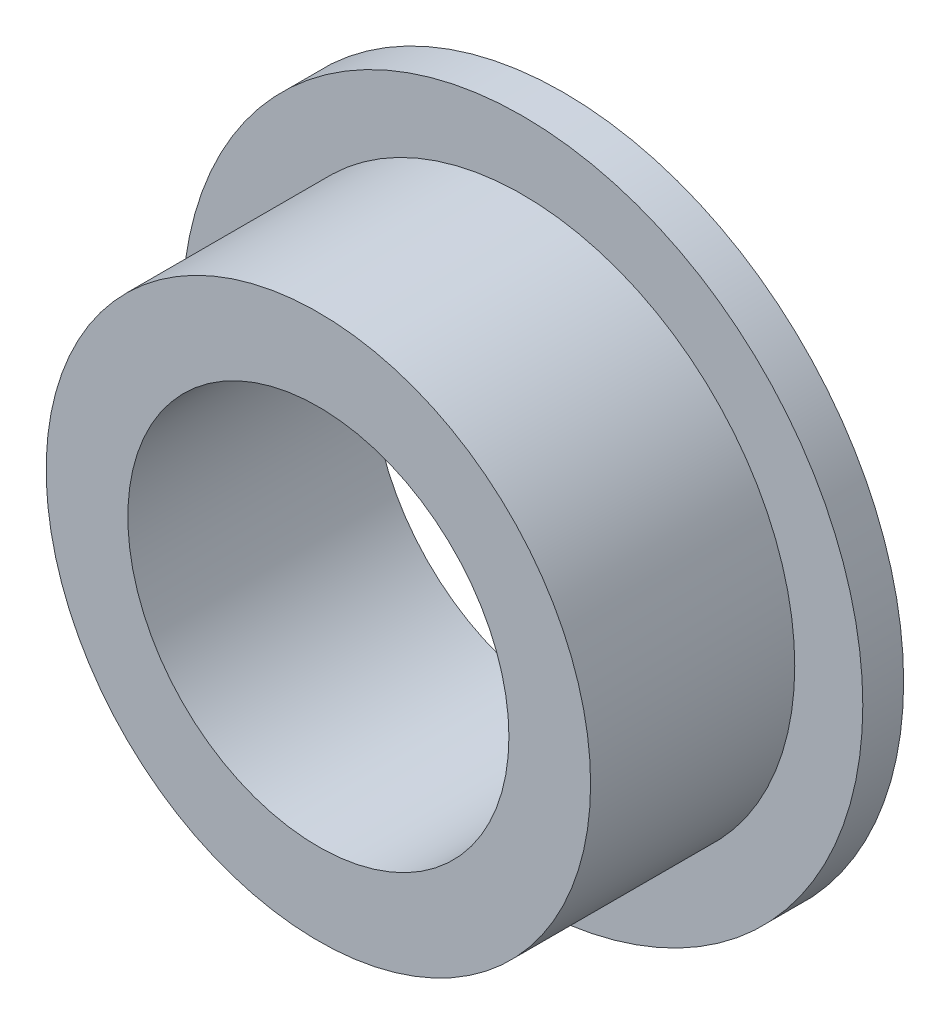
SolidWorks part; units mm, degrees
other "MotorBear"
material "Brass"
ref_plane "Front" through (0, 0, 0) normal (0, 0, 1) x (1, 0, 0)
ref_plane "Top" through (0, 0, 0) normal (0, 1, 0) x (1, 0, 0)
ref_plane "Right" through (0, 0, 0) normal (1, 0, 0) x (0, 0, -1)
sketch "Sketch1" plane through (0, 0, 0) normal (0, 0, 1) x (1, 0, 0)
  circle A0 centre (0, 0) radius 1.4
  circle A1 centre (0, 0) radius 2.5
  dimension "D1" = 2.8
  dimension "D2" = 5
extrude "Boss-Extrude1" add sketch "Sketch1" along normal blind 0.3
sketch "Sketch2" plane through (0, 0, 0.3) normal (0, 0, 1) x (1, 0, 0)
  circle A0 centre (0, 0) radius 1.4
  circle A1 centre (0, 0) radius 2
  dimension "D1" = 4
extrude "Boss-Extrude2" add sketch "Sketch2" along normal blind 1.5
